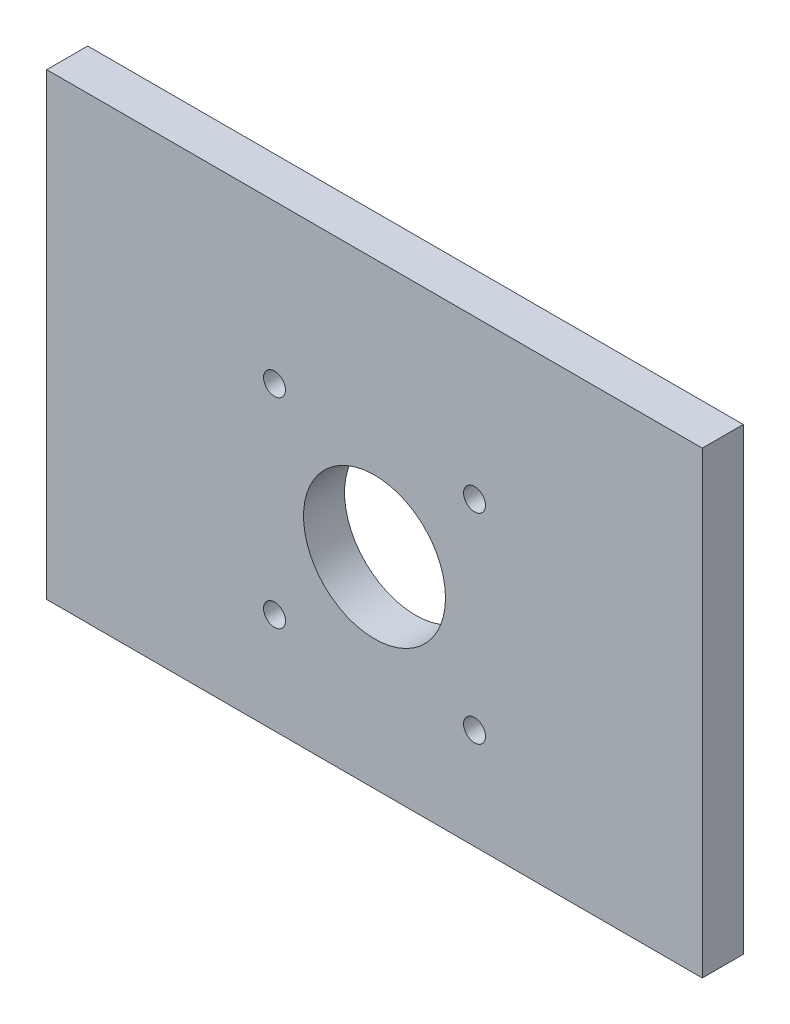
SolidWorks part; units mm, degrees
ref_plane "Front Plane" through (0, 0, 0) normal (0, 0, 1) x (1, 0, 0)
ref_plane "Top Plane" through (0, 0, 0) normal (0, 1, 0) x (1, 0, 0)
ref_plane "Right Plane" through (0, 0, 0) normal (1, 0, 0) x (0, 0, -1)
sketch "Sketch1" plane through (0, 0, 0) normal (0, 0, 1) x (1, 0, 0)
  line L1 (0, 0) -> (101.6, 0)
  line L2 (0, 0) -> (0, 71.12)
  line L3 (0, 71.12) -> (101.6, 71.12)
  line L4 (101.6, 0) -> (101.6, 71.12)
  dimension "D1" = 101.6
  dimension "D2" = 71.12
extrude "base" add sketch "Sketch1" along normal blind 6.35
hole_wizard "motor mounting holes" positions "Sketch2" profile "Sketch3" hole size "M3" standard "ANSI Metric" end condition through all
sketch "Sketch2" plane through (0, 0, 6.35) normal (0, 0, 1) x (1, 0, 0)
  line L1 (35.3, 46.615) -> (66.3, 46.615)
  line L2 (35.3, 46.615) -> (35.3, 15.615)
  line L3 (35.3, 15.615) -> (66.3, 15.615)
  line L4 (66.3, 46.615) -> (66.3, 15.615)
  line L6 (101.6, 71.12) -> (0, 71.12) construction
  line L7 (101.6, 0) -> (101.6, 71.12) construction
  point P0 (35.3, 46.615)
  point P1 (66.3, 15.615)
  point P130 (35.3, 15.615)
  point P131 (66.3, 46.615)
  point P139 (67.1172, 21.0258)
  point P140 (35.3, 31.115)
  point P143 (50.8, 46.615)
  dimension "D1" = 31
  dimension "D2" = 40.005
  dimension "D3" = 50.8
sketch "Sketch3" plane through (35.3, 46.615, 6.35) normal (1, 0, 0) x (0, -1, 0)
  line L0 (0, 0) -> (0, 6.35)
  line L1 (0, 6.35) -> (1.7, 6.35)
  line L2 (1.7, 6.35) -> (1.7, 0)
  line L5 (1.7, 0) -> (0, 0)
  line L11 (0, -6.35) -> (0, 107.95) construction
  dimension "Thru Hole Dia." = 3.4
  dimension "Thru Hole Depth" = 6.35
sketch "Sketch4" plane through (0, 0, 6.35) normal (0, 0, 1) x (1, 0, 0)
  line L0 (35.3, 46.615) -> (66.3, 15.615) construction
  line L1 (35.3, 15.615) -> (66.3, 46.615) construction
  circle A0 centre (50.8, 31.115) radius 11
  dimension "D1" = 22
extrude "Cut-Extrude1" cut sketch "Sketch4" against normal through all
equation "\"shaft_offset_y\"=40.005"
equation "\"D2@Sketch2\"=\"shaft_offset_y\""
equation "\"D3@Sketch2\"=2in"
